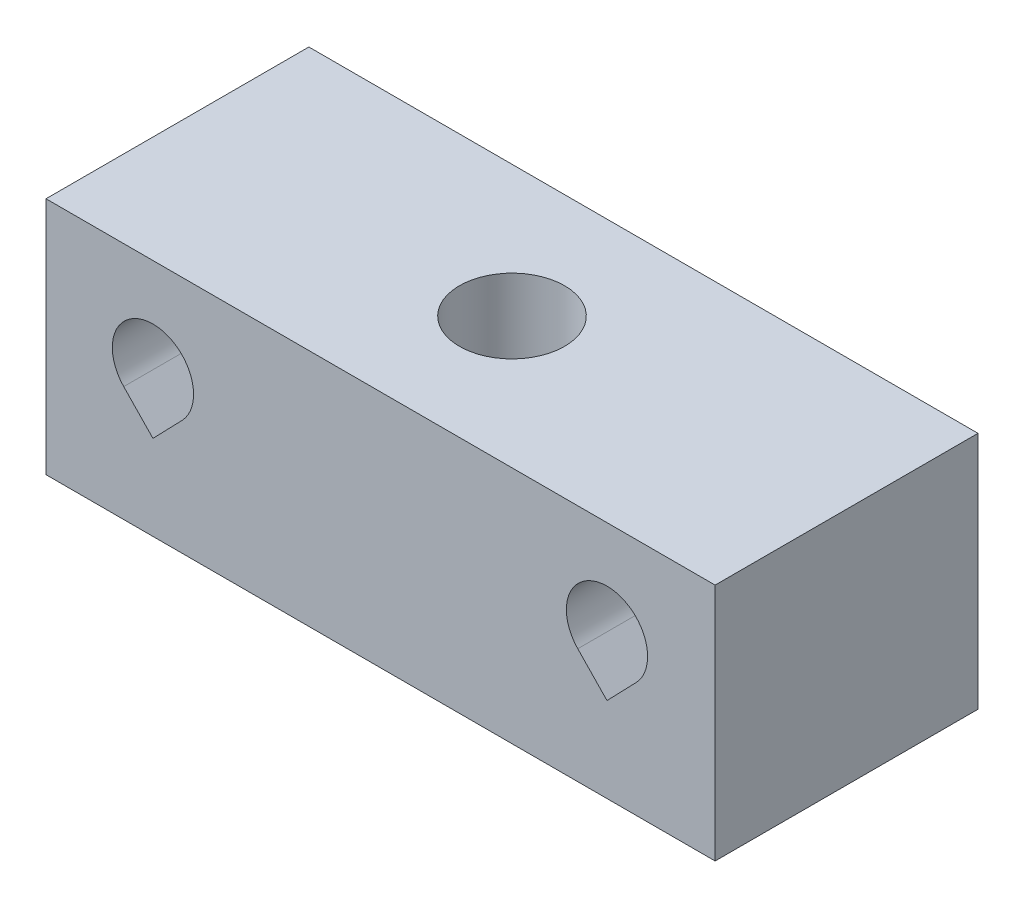
SolidWorks part; units mm, degrees
ref_plane "Front Plane" through (0, 0, 0) normal (0, 0, 1) x (1, 0, 0)
ref_plane "Top Plane" through (0, 0, 0) normal (0, 1, 0) x (1, 0, 0)
ref_plane "Right Plane" through (0, 0, 0) normal (1, 0, 0) x (0, 0, -1)
ref_plane "Plane1" through (0, -46, 0) normal (0, -1, 0) x (1, 0, 0)
sketch "Sketch1" plane through (0, -46, 0) normal (0, -1, 0) x (1, 0, 0)
  line L0 (11.95, 0) -> (39.95, 0)
  line L1 (39.95, 0) -> (39.95, 11)
  line L2 (39.95, 11) -> (11.95, 11)
  line L3 (11.95, 11) -> (11.95, 0)
extrude "Boss-Extrude1" add sketch "Sketch1" against normal blind 10
sketch "Sketch2" plane through (0, 0, 11) normal (0, 0, 1) x (1, 0, 0)
  line L0 (35.425, -42.4472) -> (36.6479, -41.1809)
  line L1 (34.2021, -41.1809) -> (35.425, -42.4472)
  arc A0 (36.6479, -41.1809) -> (34.2021, -41.1809) centre (35.425, -40) ccw
extrude "Cut-Extrude1" cut sketch "Sketch2" against normal through all
sketch "Sketch3" plane through (0, 0, 0) normal (0, 0, -1) x (-1, 0, 0)
  line L0 (-17.6479, -41.1809) -> (-16.425, -42.4472)
  line L1 (-16.425, -42.4472) -> (-15.2021, -41.1809)
  arc A0 (-15.2021, -41.1809) -> (-17.6479, -41.1809) centre (-16.425, -40) ccw
extrude "Cut-Extrude2" cut sketch "Sketch3" against normal through all
hole_wizard "Hole1" positions "Sketch5" profile "Sketch4" legacy
sketch "Sketch5" plane through (0, -46, 0) normal (0, -1, 0) x (1, 0, 0)
  point P0 (25.95, 5.5)
sketch "Sketch4" plane through (25.95, -46, 5.5) normal (1, 0, 0) x (0, 0, -1)
  line L0 (0, 0) -> (0, 10)
  line L1 (0, 10) -> (2.2, 10)
  line L2 (2.2, 10) -> (2.2, 0)
  line L3 (2.2, 0) -> (0, 0)
  line L4 (0, 110) -> (0, -10) construction
  dimension "Diameter" = 4.4
  dimension "Depth" = 10
